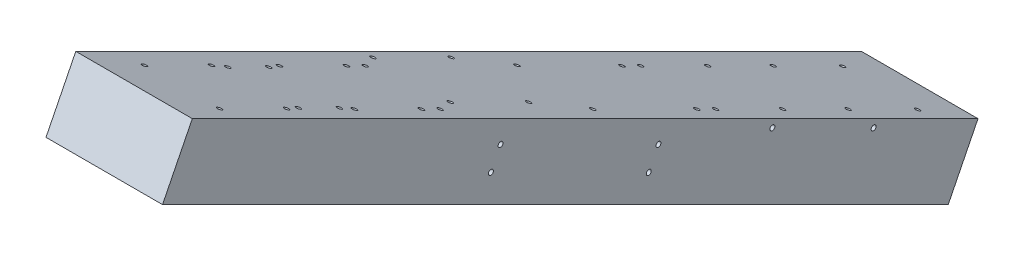
SolidWorks part; units mm, degrees
ref_plane "Спереди" through (0, 0, 0) normal (0, 0, 1) x (1, 0, 0)
ref_plane "Сверху" through (0, 0, 0) normal (0, 1, 0) x (1, 0, 0)
ref_plane "Справа" through (0, 0, 0) normal (1, 0, 0) x (0, 0, -1)
ref_plane "Плоскость4" through (35, -236.5771, 8.4045) normal (0, -0.8944, 0.4472) x (0, -0.4472, -0.8944)
sketch "Эскиз2" plane through (35, -236.5771, 8.4045) normal (0, -0.8944, 0.4472) x (0, -0.4472, -0.8944)
  line L0 (-280.1542, 70) -> (775.1738, 70)
  line L2 (775.1738, -70) -> (-280.1542, -70)
  line L3 (-112.4848, -40) -> (-112.4848, -35) construction
  line L4 (-280.1542, -70) -> (-280.1542, 70)
  line L5 (775.1738, 70) -> (775.1738, -70)
  circle A0 centre (-220.1542, 49) radius 3
  circle A1 centre (-130.1542, 49) radius 3
  circle A2 centre (-220.1542, -41) radius 3
  circle A3 centre (-130.1542, -41) radius 3
  circle A4 centre (-40, 50) radius 3
  circle A5 centre (-40, -40) radius 3
  circle A6 centre (50, 50) radius 3
  circle A7 centre (50, -40) radius 3
  circle A8 centre (75, 50) radius 3
  circle A9 centre (75, -40) radius 3
  circle A12 centre (105, -57.5) radius 3
  circle A13 centre (105, 35.5) radius 3
  circle A14 centre (210, -57.5) radius 3
  circle A15 centre (210, 35.5) radius 3
  circle A18 centre (280, 50) radius 3
  circle A20 centre (280, -41) radius 3
  circle A21 centre (420, 50) radius 3
  circle A22 centre (420, -40) radius 3
  circle A23 centre (445, 50) radius 3
  circle A24 centre (445, -40) radius 3
  circle A25 centre (535, 50) radius 3
  circle A26 centre (535, -40) radius 3
  circle A27 centre (623, 50) radius 3
  circle A28 centre (715.1738, 51) radius 3
  circle A29 centre (623, -40) radius 3
  circle A30 centre (715.1738, -39) radius 3
  circle A31 centre (-57.5, -37.5) radius 3
  circle A32 centre (-57.5, 47.5) radius 3
  circle A33 centre (-112.5, 47.5) radius 3
  circle A34 centre (-112.4848, -37.5) radius 2.9848
  point P81 (0, 0)
  point P82 (0, 0)
extrude "Бобышка-Вытянуть1" add sketch "Эскиз2" along normal blind 80
ref_plane "Плоскость5" through (105, 0, 0) normal (1, 0, 0) x (0, 0, -1)
sketch "Эскиз3" plane through (105, 0, 0) normal (1, 0, 0) x (0, 0, -1)
  circle A1 centre (301.0027, -418.1135) radius 3
  circle A2 centre (289.3752, -441.3686) radius 3
  circle A3 centre (437.903, -469.3344) radius 3
  circle A4 centre (559.5451, -530.1554) radius 3
  circle A5 centre (111.3842, -323.3043) radius 3
  circle A6 centre (99.7566, -346.5594) radius 3
extrude "Вырез-Вытянуть1" cut sketch "Эскиз3" against normal blind 10
